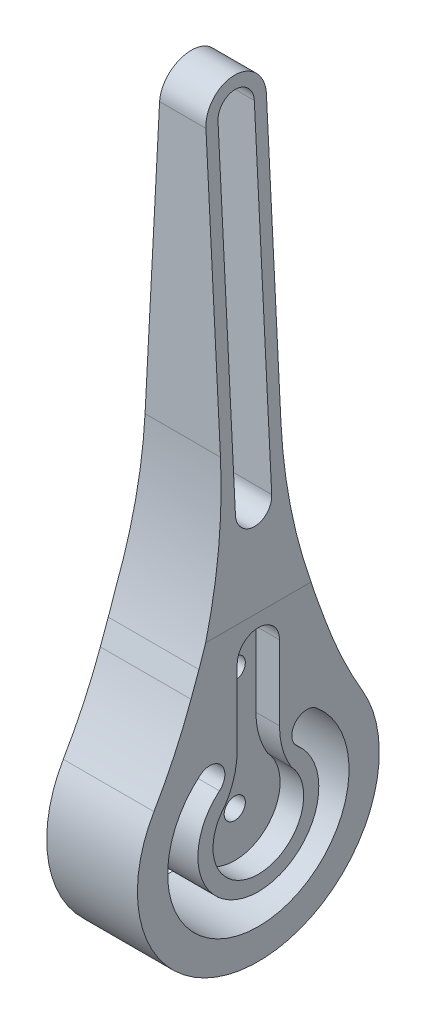
SolidWorks part; units mm, degrees
material "PLA- Generic"
ref_plane "Front Plane" through (0, 0, 0) normal (1, 0, 0) x (0, 1, 0)
ref_plane "Top Plane" through (0, 0, 0) normal (0, 0, 1) x (0, 1, 0)
ref_plane "Right Plane" through (0, 0, 0) normal (0, 1, 0) x (-1, 0, 0)
other "Center of Mass"
sketch "Sketch2" plane through (0, 0, 0) normal (1, 0, 0) x (0, 1, 0)
  line L0 (0, 0) -> (100, 0) construction
  line L1 (40, 5) -> (40, -5) construction
  line L2 (54.1062, 5) -> (100, 5)
  line L3 (26.7445, 9.8246) -> (23.1357, 11.1381)
  line L4 (54.1062, -5) -> (100, -5)
  line L5 (26.7445, -9.8246) -> (23.1357, -11.1381)
  line L6 (45, 3) -> (100, 3)
  line L7 (45, -3) -> (100, -3)
  arc A0 (10.0995, 17.2627) -> (10.0995, -17.2627) centre (0, 0) ccw
  arc A1 (100, -5) -> (100, 5) centre (100, 0) ccw
  arc A2 (26.7445, 9.8246) -> (54.1062, 5) centre (54.1062, 85) ccw
  arc A3 (23.1357, 11.1381) -> (10.0995, 17.2627) centre (50.4973, 86.3135) cw
  arc A4 (26.7445, -9.8246) -> (54.1062, -5) centre (54.1062, -85) cw
  arc A5 (23.1357, -11.1381) -> (10.0995, -17.2627) centre (50.4973, -86.3135) ccw
  arc A6 (45, 3) -> (45, -3) centre (45, 0) ccw
  arc A7 (100, -3) -> (100, 3) centre (100, 0) ccw
  point P7 (40, 0)
  dimension "D2" = 40
  dimension "D3" = 10
  dimension "D7" = 80
  dimension "D8" = 80
  dimension "D10" = 6
  dimension "D1" = 100
  dimension "D4" = 40
  dimension "D5" = 5
  dimension "D6" = 160
  dimension "D9" = 45
extrude "Boss-Extrude1" add sketch "Sketch2" against normal blind 15
sketch "Sketch3" plane through (0, 0, 0) normal (1, 0, 0) x (0, 1, 0)
  line L12 (24.3305, 3.5) -> (12, 3.5)
  line L13 (24.3305, -3.5) -> (12, -3.5)
  line L14 (12, 3.5) -> (12, -3.5) construction
  arc A31 (5.1536, 5.4489) -> (5.1536, -5.4489) centre (0, 0) ccw
  arc A32 (12, 3.5) -> (5.1536, 5.4489) centre (12, 16.5) cw
  arc A33 (12, -3.5) -> (5.1536, -5.4489) centre (12, -16.5) ccw
  arc A34 (24.3305, -3.5) -> (24.3305, 3.5) centre (24.3305, 0) ccw
  dimension "D1" = 12
  dimension "D2" = 15
  dimension "D4" = 13
  dimension "D3" = 24.3305
extrude "Cut-Extrude1" cut sketch "Sketch3" against normal blind 3.9
sketch "Sketch4" plane through (-3.9, 0, 0) normal (1, 0, 0) x (0, 1, 0)
  line L0 (0, 0) -> (28.5722, 0) construction
  circle A0 centre (20, 0) radius 1.75
  circle A1 centre (24, 0) radius 1.75
  circle A2 centre (0, 0) radius 1.75
  dimension "D1" = 3.5
  dimension "D2" = 20
  dimension "D4" = 3.5
  dimension "D3" = 24
extrude "Cut-Extrude2" cut sketch "Sketch4" against normal through all
sketch "Sketch5" plane through (0, 0, 0) normal (0, 0, 1) x (0, 1, 0)
  line L0 (30, 15) -> (30, 0) construction
  line L1 (30, 15) -> (105, 11.0694)
  line L2 (54.1062, 15) -> (26.7445, 15) construction
  line L3 (100, 15) -> (54.1062, 15) construction
  line L4 (-20, 7.5) -> (105, 7.5) construction
  line L5 (-20, 15) -> (-20, 0) construction
  line L8 (105, 0) -> (105, 15) construction
  line L10 (30, 15) -> (105, 15)
  line L11 (105, 15) -> (105, 11.0694)
  line L12 (105, 0) -> (105, 3.9306)
  line L13 (30, 0) -> (105, 3.9306)
  line L14 (30, 0) -> (105, 0)
  dimension "D1" = 30
  dimension "D2" = 3
extrude "Cut-Extrude3" cut sketch "Sketch5" against normal through all both and the other way through all
sketch "Sketch8" plane through (0, 0, 0) normal (1, 0, 0) x (0, 1, 0)
  line L0 (0, 0) -> (11.4907, 9.6418) construction
  line L1 (0, 0) -> (16.25, 0) construction
  line L2 (0, 0) -> (11.4907, -9.6418) construction
  arc A0 (9.5756, 8.0348) -> (9.5756, -8.0348) centre (0, 0) ccw construction
  arc A1 (11.4907, 9.6418) -> (11.4907, -9.6418) centre (0, 0) ccw
  arc A2 (7.6604, 6.4279) -> (7.6604, -6.4279) centre (0, 0) ccw
  circle A3 centre (0, 0) radius 10 construction
  circle A4 centre (0, 0) radius 12.5 construction
  circle A5 centre (0, 0) radius 15 construction
  arc A6 (7.6604, 6.4279) -> (11.4907, 9.6418) centre (9.5756, 8.0348) ccw
  arc A7 (7.6604, -6.4279) -> (11.4907, -9.6418) centre (9.5756, -8.0348) cw
  dimension "D1" = 25
  dimension "D4" = 40
  dimension "D2" = 2.5
  dimension "D3" = 2.5
extrude "Cut-Extrude5" cut sketch "Sketch8" against normal through all
ref_plane "Plane1" through (-7.5, 0, 0) normal (1, 0, 0) x (0, 0, -1)
